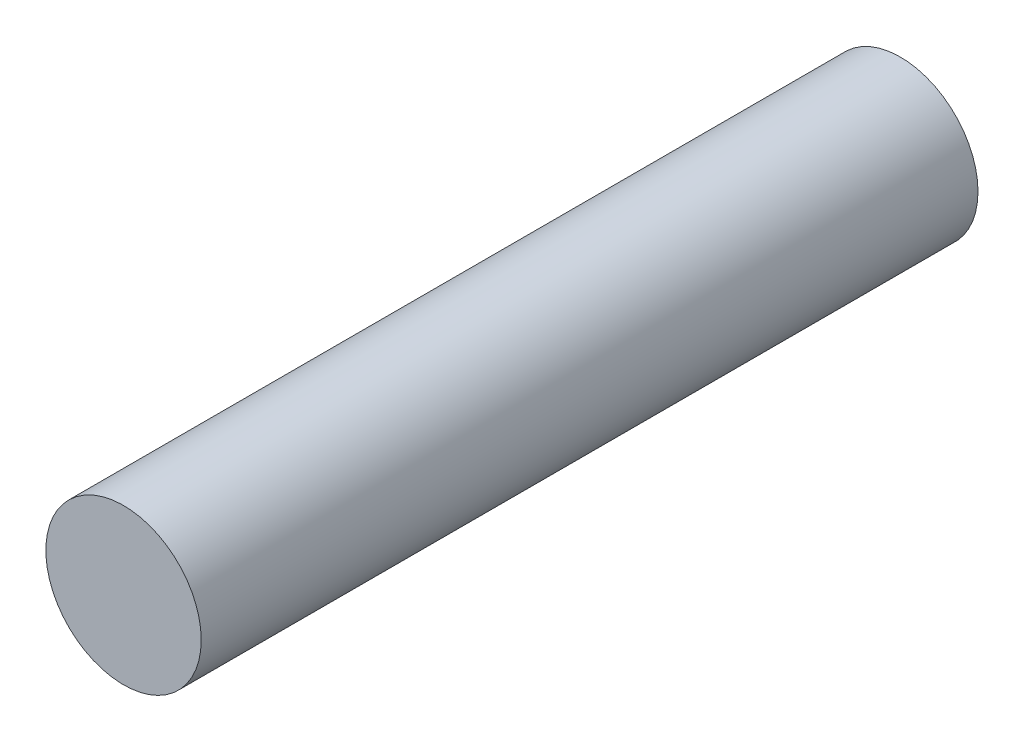
SolidWorks part; units mm, degrees
material "Chrome Stainless Steel"
ref_plane "Front Plane" through (0, 0, 0) normal (0, 0, 1) x (1, 0, 0)
ref_plane "Top Plane" through (0, 0, 0) normal (0, 1, 0) x (1, 0, 0)
ref_plane "Right Plane" through (0, 0, 0) normal (1, 0, 0) x (0, 0, -1)
sketch "Sketch2" plane through (0, 0, 0) normal (0, 0, 1) x (1, 0, 0)
  circle A0 centre (0, 0) radius 7.5
  dimension "D1" = 15
extrude "Boss-Extrude1" add sketch "Sketch2" along normal blind 75
